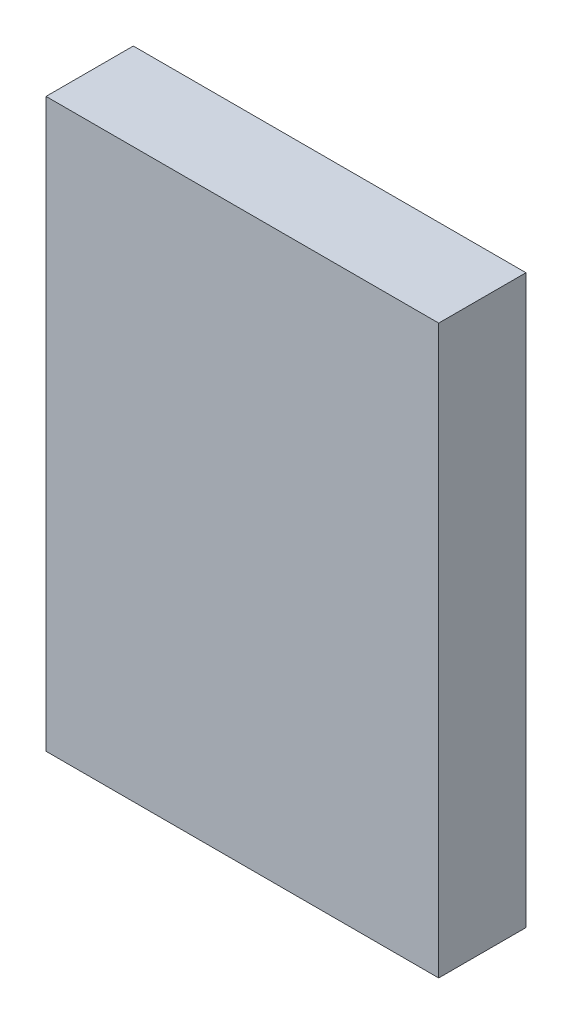
SolidWorks part; units mm, degrees
ref_plane "Plan de face" through (0, 0, 0) normal (0, 0, 1) x (1, 0, 0)
ref_plane "Plan de dessus" through (0, 0, 0) normal (0, 1, 0) x (1, 0, 0)
ref_plane "Plan de droite" through (0, 0, 0) normal (1, 0, 0) x (0, 0, -1)
sketch "Esquisse1" plane through (0, 0, 0) normal (0, 0, 1) x (1, 0, 0)
  line L1 (-28.575, 41.275) -> (28.575, 41.275)
  line L2 (-28.575, 41.275) -> (-28.575, -41.275)
  line L3 (-28.575, -41.275) -> (28.575, -41.275)
  line L4 (28.575, 41.275) -> (28.575, -41.275)
  line L5 (-28.575, 41.275) -> (28.575, -41.275) construction
  line L6 (-28.575, -41.275) -> (28.575, 41.275) construction
  point P0 (0, 0)
  dimension "D1" = 82.55
  dimension "D2" = 57.15
extrude "Boss.-Extru.1" add sketch "Esquisse1" along normal blind 12.7
